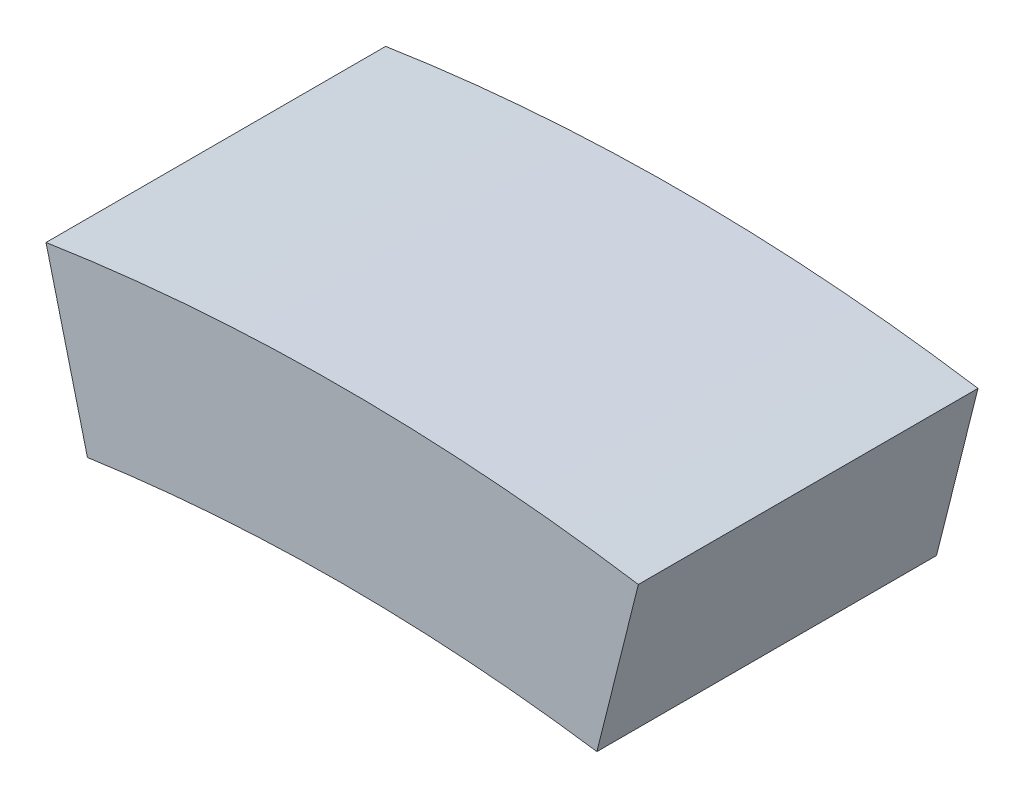
SolidWorks part; units mm, degrees
ref_plane "Front Plane" through (0, 0, 0) normal (0, 0, 1) x (1, 0, 0)
ref_plane "Top Plane" through (0, 0, 0) normal (0, 1, 0) x (1, 0, 0)
ref_plane "Right Plane" through (0, 0, 0) normal (1, 0, 0) x (0, 0, -1)
sketch "Sketch3" plane through (0, 0, 0) normal (0, 0, 1) x (1, 0, 0)
  line L0 (0, 0) -> (-2.4409, 9.7458)
  line L1 (15, 0) -> (15, 11.084) construction
  line L2 (30, 0) -> (32.4409, 9.7458)
  line L3 (0, 0) -> (30, 0) construction
  arc A0 (30, 0) -> (0, 0) centre (15, -103.2395) ccw
  arc A1 (32.4409, 9.7458) -> (-2.4409, 9.7458) centre (15, -103.2395) ccw
  point P7 (0, 0)
  point P8 (30, 0)
  dimension "D2" = 10
  dimension "D1" = 114.3235
  dimension "D3" = 30
extrude "Boss-Extrude1" add sketch "Sketch3" along normal mid plane 20
